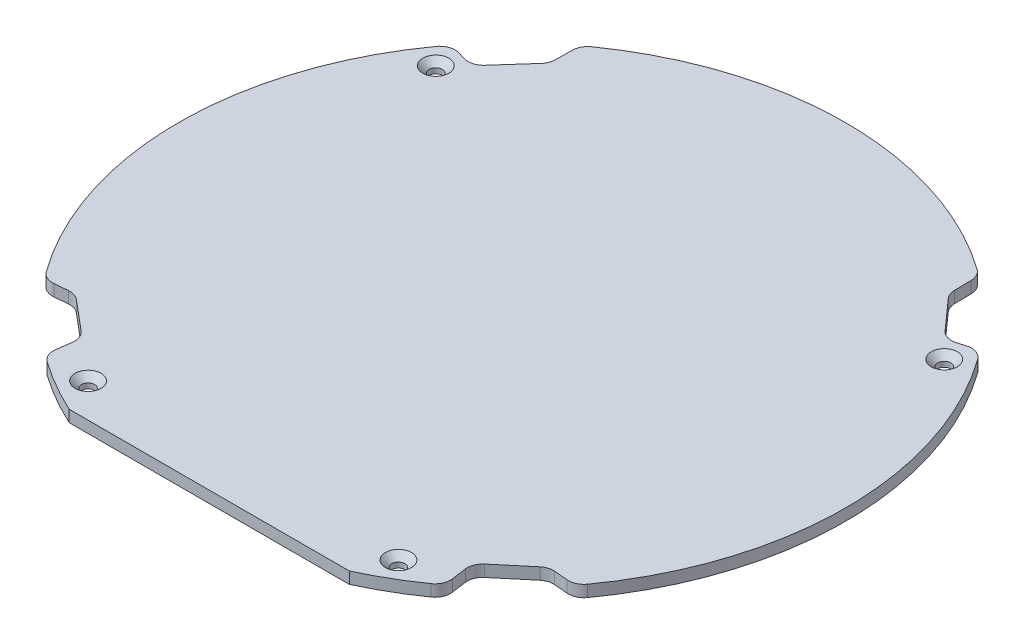
SolidWorks part; units mm, degrees
ref_plane "Plano frontal" through (0, 0, 0) normal (0, 0, 1) x (1, 0, 0)
ref_plane "Plano superior" through (0, 0, 0) normal (0, 1, 0) x (1, 0, 0)
ref_plane "Plano direito" through (0, 0, 0) normal (1, 0, 0) x (0, 0, -1)
sketch "Esboço1" plane through (0, 0, 0) normal (0, 1, 0) x (1, 0, 0)
  line L0 (-68.0899, 52.5335) -> (-60.9902, 50.4152)
  line L1 (36.1, -78.0563) -> (-36.1, -78.0563)
  line L2 (0, -78.0563) -> (0, 153.958) construction
  line L3 (60.4773, 60.4773) -> (-60.4773, -60.4773) construction
  line L8 (-60.4773, 60.4773) -> (60.4773, -60.4773) construction
  line L9 (-60.9902, 50.4152) -> (-51.4745, 61.095)
  line L10 (-51.4745, 61.095) -> (-51.3663, 68.9746)
  line L11 (68.0899, 52.5335) -> (60.9902, 50.4152)
  line L12 (60.9902, 50.4152) -> (51.4745, 61.095)
  line L13 (51.4745, 61.095) -> (51.3663, 68.9746)
  line L14 (0, 0) -> (58.1676, 0) construction
  line L15 (-68.3935, -52.1375) -> (-60.9902, -51.5129)
  line L16 (-60.9902, -51.5129) -> (-50.3187, -60.4773)
  line L17 (-50.3187, -60.4773) -> (-51.4745, -68.8939)
  line L18 (68.3935, -52.1375) -> (60.9902, -51.5129)
  line L19 (50.3187, -60.4773) -> (51.4745, -68.8939)
  line L20 (60.9902, -51.5129) -> (50.3187, -60.4773)
  arc A0 (36.1, -78.0563) -> (51.4745, -68.8939) centre (0, 0) ccw
  arc A1 (-51.4745, -68.8939) -> (-36.1, -78.0563) centre (0, 0) ccw
  arc A2 (68.3935, -52.1375) -> (68.0899, 52.5335) centre (0, 0) ccw
  arc A3 (51.3663, 68.9746) -> (-51.3663, 68.9746) centre (0, 0) ccw
  arc A4 (-68.0899, 52.5335) -> (-68.3935, -52.1375) centre (0, 0) ccw
  point P8 (0, -78.0563)
  point P9 (70.3405, -49.4794)
  point P12 (68.0899, -51.906)
  point P13 (60.9902, -51.5129)
  point P14 (-60.4773, -60.4773)
  point P17 (-60.4773, 60.4773)
  point P18 (50.3187, -60.4773)
  point P23 (-48.4357, -60.4773)
  point P32 (-60.0496, -50.5053)
  point P37 (51.4745, -68.8939)
  point P38 (-51.4745, 68.9746)
  point P39 (-51.3663, 61.095)
  point P40 (0, 0)
  point P41 (-60.9902, 50.4152)
  dimension "D1" = 172
  dimension "D2" = 36.1
  dimension "D3" = 45
  dimension "D4" = 45
extrude "Ressalto-extrusão1" add sketch "Esboço1" along normal blind 3
hole_wizard "Escareado para SFHCS M31" positions "Esboço5" profile "Esboço3" countersink size "M3" standard "Ansi Metric" end condition through all
sketch "Esboço5" plane through (0, 3, 0) normal (0, 1, 0) x (1, 0, 0)
  line L0 (0, 0) -> (0, 47.8911) construction
  line L2 (65.5322, 45.8861) -> (0, 0) construction
  line L3 (0, 0) -> (40, -69.282) construction
  point P0 (40, -69.282)
  point P2 (65.5322, 45.8861)
  point P20 (-40, -69.282)
  point P21 (-65.5322, 45.8861)
  dimension "D1" = 55
  dimension "D2" = 30
  dimension "D3" = 80
  dimension "D4" = 80
sketch "Esboço3" plane through (40, 3, 69.282) normal (1, 0, 0) x (0, 0, 1)
  line L0 (0, 0) -> (0, 3)
  line L1 (0, 3) -> (1.7, 3)
  line L2 (1.7, 3) -> (1.7, 1.66)
  line L3 (1.7, 1.66) -> (3.36, 0)
  line L5 (3.36, 0) -> (0, 0)
  line L6 (-1.7, 1.66) -> (-3.36, 0) construction
  line L11 (0, -6.35) -> (0, 107.95) construction
  dimension "Thru Hole Dia." = 3.4
  dimension "Thru Hole Depth" = 3
  dimension "Near C'Sink Dia." = 6.72
  dimension "Near C'Sink Angle" = 90
fillet "Filete1" radius 4 16 edges at (-68.0899, 1.5, -52.5335) (-60.9902, 1.5, -50.4152) (-51.4745, 1.5, -61.095) (-51.3663, 1.5, -68.9746) (51.3663, 1.5, -68.9746) (51.4745, 1.5, -61.095) (60.9902, 1.5, -50.4152) (68.0899, 1.5, -52.5335) (68.3935, 1.5, 52.1375) (60.9902, 1.5, 51.5129) (51.4745, 1.5, 68.8939) (50.3187, 1.5, 60.4773) (-51.4745, 1.5, 68.8939) (-50.3187, 1.5, 60.4773) (-60.9902, 1.5, 51.5129) (-68.3935, 1.5, 52.1375)
